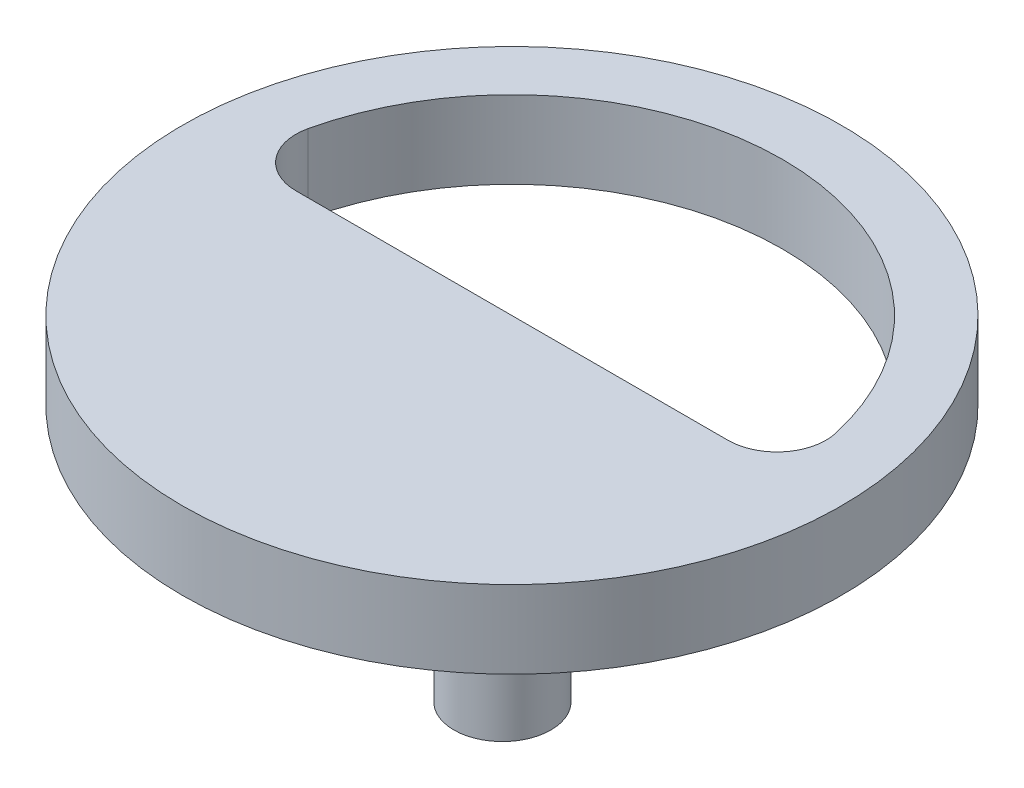
SolidWorks part; units mm, degrees
material "ABS"
ref_plane "Front Plane" through (0, 0, 0) normal (0, 0, 1) x (1, 0, 0)
ref_plane "Top Plane" through (0, 0, 0) normal (0, 1, 0) x (1, 0, 0)
ref_plane "Right Plane" through (0, 0, 0) normal (1, 0, 0) x (0, 0, -1)
sketch "Эскиз1" plane through (0, 0, 0) normal (0, 1, 0) x (1, 0, 0)
  line L0 (5.5656, 0) -> (-5.5656, 0)
  circle A0 centre (0, 0) radius 8.4903
  arc A1 (5.5656, 0) -> (6.797, 1.542) centre (5.5656, 1.2626) ccw
  arc A2 (-6.797, 1.542) -> (-5.5656, 0) centre (-5.5656, 1.2626) ccw
  arc A3 (6.797, 1.542) -> (-6.797, 1.542) centre (0, 0) ccw
  dimension "D1" = 16.9805
  dimension "D2" = 1.2626
  dimension "D3" = 6.9697
extrude "Бобышка-Вытянуть1" add sketch "Эскиз1" along normal blind 2
sketch "Эскиз2" plane through (0, 0, 0) normal (0, -1, 0) x (1, 0, 0)
  line L0 (0, 0) -> (0, -27) construction
  line L1 (0, 0) -> (0, 8.4903) construction
  line L2 (0, 0) -> (-27, 0) construction
  line L3 (0, 0) -> (27, 0) construction
  line L5 (0, 4.2451) -> (-4, 4.2451) construction
  line L6 (0, 4.2451) -> (4, 4.2451) construction
  circle A4 centre (-4, 4.2451) radius 1.25
  circle A5 centre (4, 4.2451) radius 1.25
  dimension "D1" = 2.5
  dimension "D2" = 2.797
  dimension "D3" = 6.797
  dimension "D4" = 4.2451
extrude "Бобышка-Вытянуть2" add sketch "Эскиз2" along normal blind 2.5
